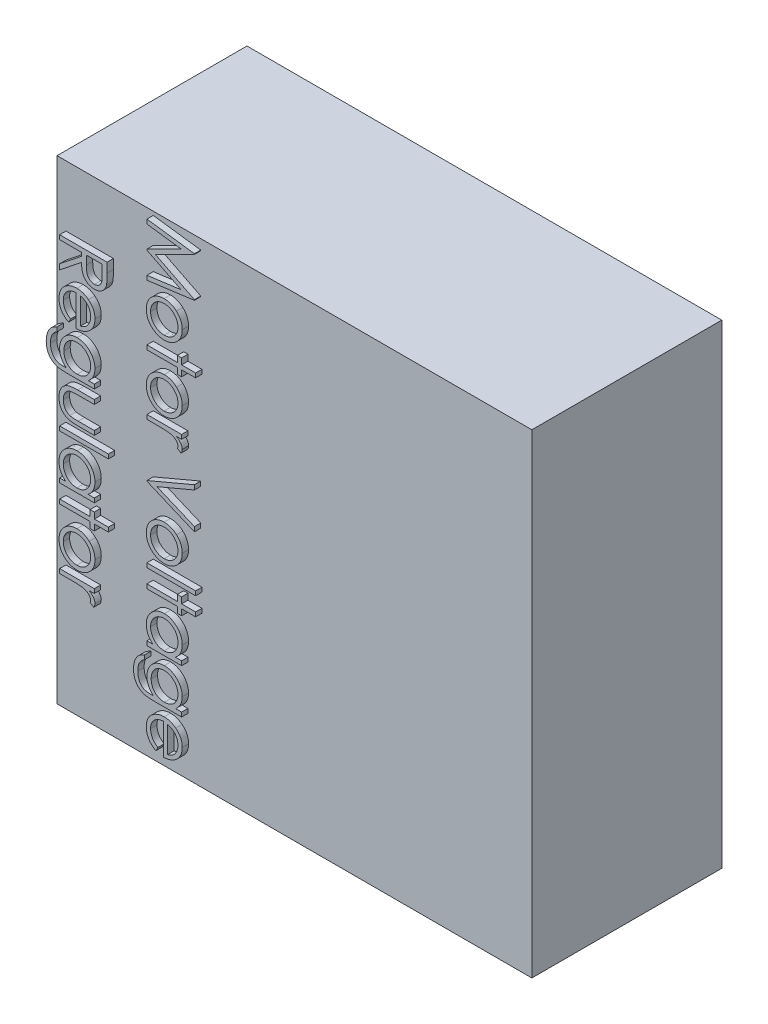
SolidWorks part; units mm, degrees
ref_plane "Front Plane" through (0, 0, 0) normal (0, 0, 1) x (1, 0, 0)
ref_plane "Top Plane" through (0, 0, 0) normal (0, 1, 0) x (1, 0, 0)
ref_plane "Right Plane" through (0, 0, 0) normal (1, 0, 0) x (0, 0, -1)
sketch "Sketch1" plane through (0, 0, 0) normal (0, 0, 1) x (1, 0, 0)
  line L1 (-37.5, -37.5) -> (37.5, -37.5)
  line L2 (-37.5, -37.5) -> (-37.5, 37.5)
  line L3 (-37.5, 37.5) -> (37.5, 37.5)
  line L4 (37.5, -37.5) -> (37.5, 37.5)
  line L5 (0, 37.5) -> (0, -37.5) construction
  line L6 (-37.5, 0) -> (37.5, 0) construction
  point P0 (0, 0)
  dimension "D1" = 75
  dimension "D2" = 75
extrude "Boss-Extrude1" add sketch "Sketch1" along normal blind 30
sketch "Sketch2" plane through (0, 0, 30) normal (0, 0, 1) x (1, 0, 0)
  line L0 (-22.306, 37.5) -> (-22.306, -37.5) construction
  line L5 (37.5, 37.5) -> (-37.5, 37.5) construction
  line L6 (-37.5, -37.5) -> (37.5, -37.5) construction
  text T0 "Motor Voltage \r\n   Regulator" font "Century Gothic" height 7.5
extrude "Boss-Extrude2" add sketch "Sketch2" along normal blind 1
